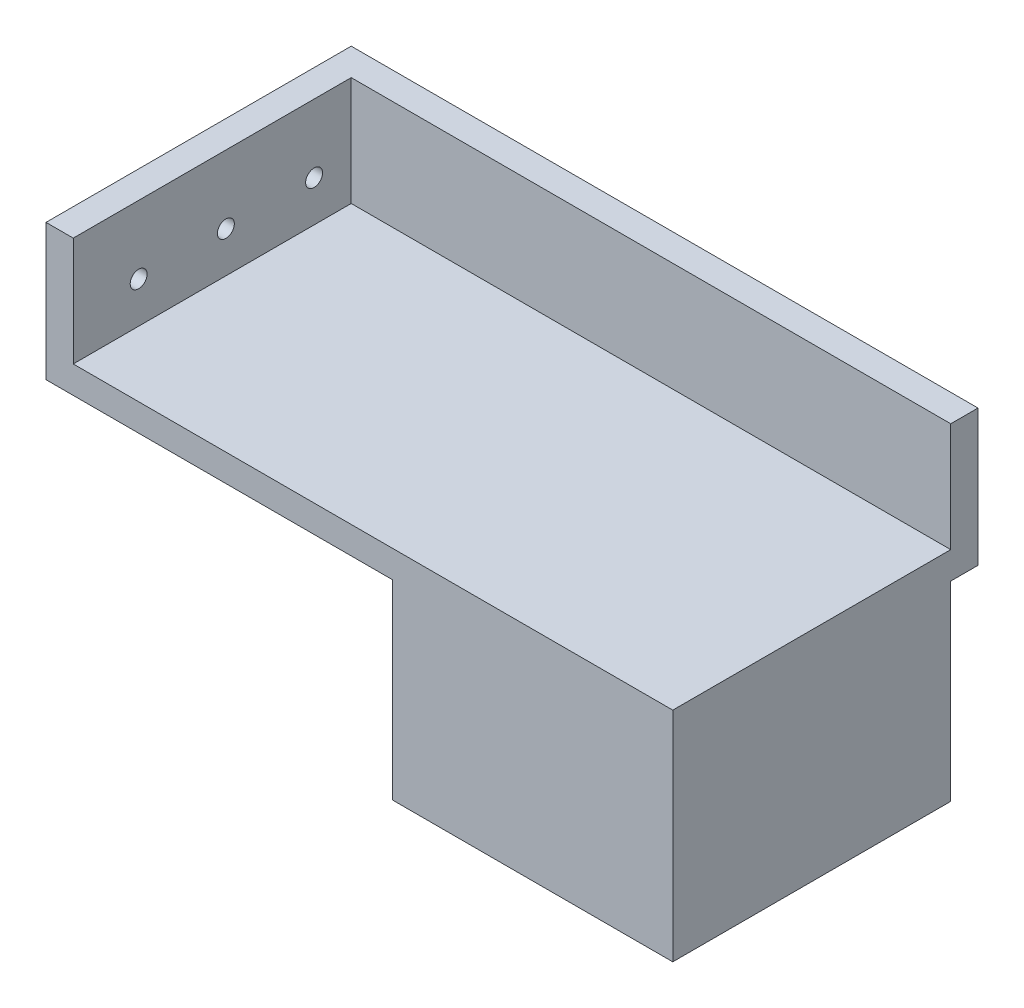
SolidWorks part; units mm, degrees
ref_plane "前视基准面" through (0, 0, 0) normal (0, 0, 1) x (1, 0, 0)
ref_plane "上视基准面" through (0, 0, 0) normal (0, 1, 0) x (1, 0, 0)
ref_plane "右视基准面" through (0, 0, 0) normal (1, 0, 0) x (0, 0, -1)
sketch "草图1" plane through (0, 0, 0) normal (0, 1, 0) x (1, 0, 0)
  line L1 (-42.3145, 16.5887) -> (67.6855, 16.5887)
  line L2 (-42.3145, 16.5887) -> (-42.3145, -34.4113)
  line L3 (-42.3145, -34.4113) -> (67.6855, -34.4113)
  line L4 (67.6855, 16.5887) -> (67.6855, -34.4113)
  line L5 (-42.3145, 16.5887) -> (67.6855, -34.4113) construction
  line L6 (-42.3145, -34.4113) -> (67.6855, 16.5887) construction
  point P4 (12.6855, -8.9113)
  dimension "D1" = 110
  dimension "D2" = 51
extrude "凸台-拉伸1" add sketch "草图1" along normal blind 5
sketch "草图2" plane through (0, 0, 0) normal (0, -1, 0) x (1, 0, 0)
  line L1 (-42.3145, 34.4113) -> (-47.3145, 34.4113)
  line L2 (-42.3145, 34.4113) -> (-42.3145, -16.5887)
  line L4 (-47.3145, 34.4113) -> (-47.3145, -16.5887)
  line L5 (-42.3145, 34.4113) -> (-47.3145, -16.5887) construction
  line L6 (-42.3145, -16.5887) -> (-47.3145, 34.4113) construction
  line L7 (-42.3145, -16.5887) -> (67.6855, -16.5887)
  line L8 (-47.3145, -16.5887) -> (-47.3145, -21.5887)
  line L9 (-47.3145, -21.5887) -> (67.6855, -21.5887)
  line L10 (67.6855, -16.5887) -> (67.6855, -21.5887)
  line L11 (10.1855, -19.0887) -> (67.6855, -21.5887) construction
  line L12 (-47.3145, -21.5887) -> (67.6855, -16.5887) construction
  point P4 (-44.8145, 8.9113)
  point P9 (10.1855, -19.0887)
  dimension "D1" = 5
  dimension "D2" = 5
extrude "凸台-拉伸2" add sketch "草图2" against normal blind 25 separate body
sketch "草图3" plane through (-47.3145, 0, 0) normal (-1, 0, 0) x (0, 0, 1)
  line L0 (-21.5887, 12.5) -> (34.4113, 12.5) construction
  line L1 (-21.5887, 25) -> (-21.5887, 0) construction
  line L2 (34.4113, 25) -> (34.4113, 0) construction
  circle A0 centre (-9.7759, 12.5) radius 1.55
  circle A1 centre (6.4113, 12.5) radius 1.55
  circle A2 centre (22.4113, 12.5) radius 1.55
  dimension "D1" = 12
  dimension "D2" = 3.1
extrude "切除-拉伸1" cut sketch "草图3" against normal through all
sketch "草图4" plane through (0, 0, 0) normal (0, -1, 0) x (1, 0, 0)
  line L0 (-47.3145, -21.5887) -> (67.6855, -21.5887) construction
  line L1 (67.6855, 34.4113) -> (62.6855, 34.4113)
  line L2 (67.6855, 34.4113) -> (67.6855, -21.5887)
  line L3 (67.6855, -21.5887) -> (62.6855, -21.5887)
  line L4 (62.6855, 34.4113) -> (62.6855, 33.9248)
  line L7 (62.6855, 29.4113) -> (16.3015, 29.4113)
  line L8 (67.6855, 34.4113) -> (16.3015, 34.4113)
  line L9 (67.6855, 34.4113) -> (67.6855, 29.4113)
  line L10 (67.6855, 29.4113) -> (67.2391, 29.4113)
  line L11 (16.3015, 34.4113) -> (16.3015, 29.4113)
  line L13 (67.6855, 29.4113) -> (67.2429, 29.4544) construction
  line L15 (62.7286, 33.9289) -> (62.6855, 34.4113) construction
  line L16 (62.6855, 29.4113) -> (62.6855, -21.5887)
  point P4 (65.1855, 6.4113)
  point P11 (41.9935, 31.9113)
  point P18 (63.092, 29.8583)
  dimension "D1" = 5
  dimension "D2" = 5
extrude "凸台-拉伸3" add sketch "草图4" along normal blind 35
